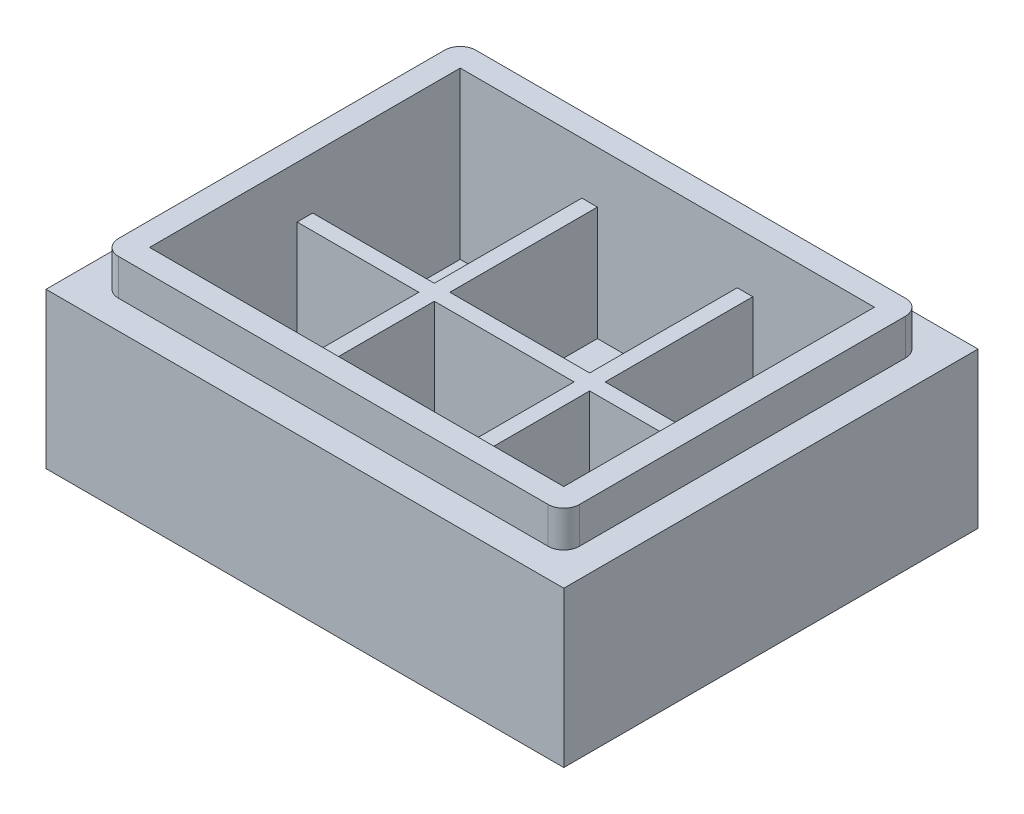
SolidWorks part; units mm, degrees
ref_plane "Front Plane" through (0, 0, 0) normal (0, 0, 1) x (1, 0, 0)
ref_plane "Top Plane" through (0, 0, 0) normal (0, 1, 0) x (1, 0, 0)
ref_plane "Right Plane" through (0, 0, 0) normal (1, 0, 0) x (0, 0, -1)
sketch "Sketch1" plane through (0, 0, 0) normal (0, 1, 0) x (1, 0, 0)
  line L1 (-50, 40) -> (50, 40)
  line L2 (-50, 40) -> (-50, -40)
  line L3 (-50, -40) -> (50, -40)
  line L4 (50, 40) -> (50, -40)
  line L5 (-50, 40) -> (50, -40) construction
  line L6 (-50, -40) -> (50, 40) construction
  point P0 (0, 0)
  dimension "D1" = 80
  dimension "D2" = 100
extrude "Boss-Extrude1" add sketch "Sketch1" along normal blind 30
sketch "Sketch2" plane through (0, 30, 0) normal (0, 1, 0) x (1, 0, 0)
  line L0 (-15, 30) -> (-15, -30) construction
  line L1 (0, 30) -> (0, -30) construction
  line L2 (16.5, -30) -> (13.5, -30)
  line L3 (13.5, 30) -> (13.5, -30)
  line L4 (16.5, 30) -> (13.5, 30)
  line L5 (-40, 1.5) -> (40, 1.5)
  line L6 (-40, 1.5) -> (-40, -1.5)
  line L7 (-40, -1.5) -> (40, -1.5)
  line L8 (40, -30) -> (40, 30)
  line L9 (40, 30) -> (-40, 30)
  line L10 (-40, 30) -> (-40, -30)
  line L11 (-40, -30) -> (40, -30)
  line L12 (40, -30) -> (40, 30)
  line L13 (40, 30) -> (-40, 30)
  line L14 (-40, 30) -> (-40, -30)
  line L15 (-40, -30) -> (40, -30)
  line L16 (40, 1.5) -> (40, -1.5)
  line L17 (-40, 1.5) -> (40, -1.5) construction
  line L18 (-40, -1.5) -> (40, 1.5) construction
  line L19 (-16.5, 30) -> (-13.5, 30)
  line L20 (-16.5, 30) -> (-16.5, -30)
  line L21 (-16.5, -30) -> (-13.5, -30)
  line L22 (-13.5, 30) -> (-13.5, -30)
  line L23 (-16.5, 30) -> (-13.5, -30) construction
  line L24 (-16.5, -30) -> (-13.5, 30) construction
  line L25 (16.5, 30) -> (16.5, -30)
  point P0 (0, 0)
  point P5 (-15, 0)
  dimension "D2" = 3
  dimension "D3" = 3
  dimension "D4" = 25
  dimension "D1" = 10
extrude "Cut-Extrude1" cut sketch "Sketch2" against normal blind 25 contours L20 L13 L14 L5 | L13 L22 L5 L3 | L13 L25 L5 L12 | L7 L25 L15 L12 | L7 L22 L15 L3 | L20 L7 L14 L15
sketch "Sketch3" plane through (0, 30, 0) normal (0, 1, 0) x (1, 0, 0)
  line L1 (-40, 30) -> (40, 30)
  line L2 (-40, 30) -> (-40, -30)
  line L3 (-40, -30) -> (40, -30)
  line L4 (40, 30) -> (40, -30)
  line L5 (-40, 30) -> (40, -30) construction
  line L6 (-40, -30) -> (40, 30) construction
  point P0 (0, 0)
extrude "Cut-Extrude2" cut sketch "Sketch3" against normal blind 3
sketch "Sketch5" plane through (0, 30, 0) normal (0, 1, 0) x (1, 0, 0)
  line L56 (-40, 30) -> (-40, -30) construction
  line L57 (-40, -30) -> (40, -30) construction
  line L58 (40, -30) -> (40, 30) construction
  line L59 (40, 30) -> (-40, 30) construction
  line L60 (-44.5, -34.5) -> (44.5, -34.5)
  line L61 (44.5, -34.5) -> (44.5, 34.5)
  line L62 (44.5, 34.5) -> (-44.5, 34.5)
  line L63 (-44.5, 34.5) -> (-44.5, -34.5)
  line L64 (-44.5, -34.5) -> (44.5, -34.5)
  line L65 (44.5, -34.5) -> (44.5, 34.5)
  line L66 (44.5, 34.5) -> (-44.5, 34.5)
  line L67 (-44.5, 34.5) -> (-44.5, -34.5)
  line L68 (-40, 30) -> (-40, -30)
  line L69 (-40, -30) -> (40, -30)
  line L70 (40, -30) -> (40, 30)
  line L71 (40, 30) -> (-40, 30)
  point P0 (0, 0)
  dimension "D1" = 5.5
extrude "Boss-Extrude2" add sketch "Sketch5" along normal blind 7
fillet "Fillet1" radius 3 4 edges at (44.5, 33.5, -34.5) (-44.5, 33.5, -34.5) (-44.5, 33.5, 34.5) (44.5, 33.5, 34.5)
